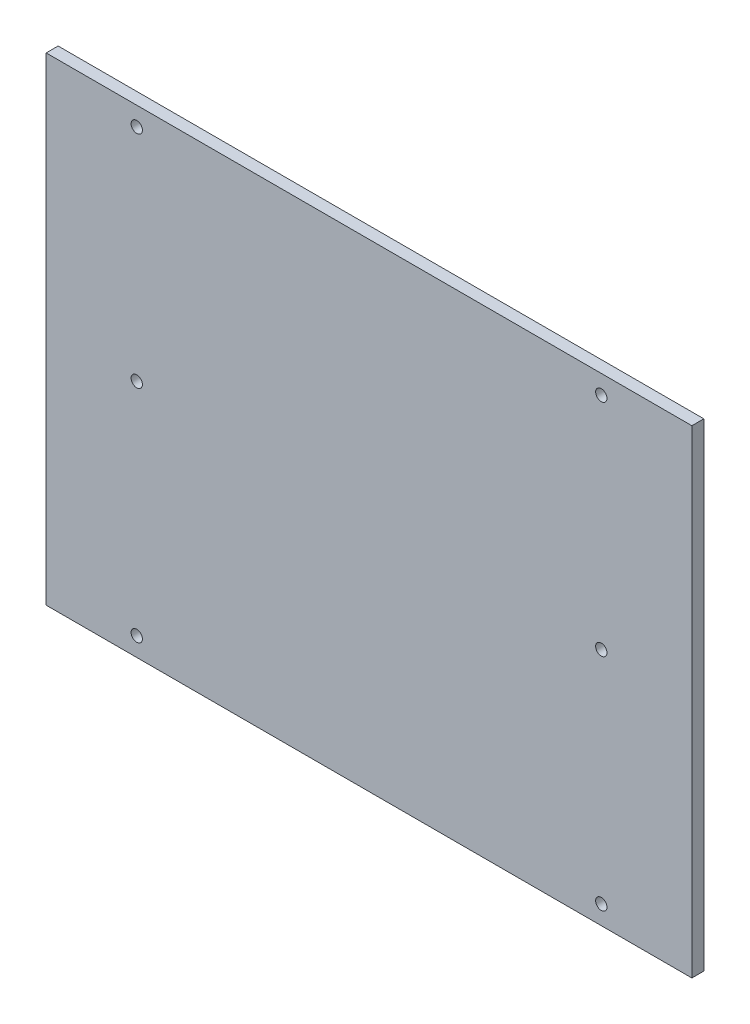
SolidWorks part; units mm, degrees
material "Acrylic (Medium-high impact)"
ref_plane "Front Plane" through (0, 0, 0) normal (0, 0, 1) x (1, 0, 0)
ref_plane "Top Plane" through (0, 0, 0) normal (0, 1, 0) x (1, 0, 0)
ref_plane "Right Plane" through (0, 0, 0) normal (1, 0, 0) x (0, 0, -1)
sketch "Sketch1" plane through (0, 0, 0) normal (0, 0, 1) x (1, 0, 0)
  line L0 (0, 0) -> (0, 127)
  line L1 (0, 127) -> (133.35, 127)
  line L2 (133.35, 127) -> (133.35, 0)
  line L3 (133.35, 0) -> (0, 0)
  line L8 (66.675, 127) -> (66.675, 0) construction
  line L9 (0, 63.5) -> (133.35, 63.5) construction
  circle A0 centre (5, 5) radius 1.5
  circle A1 centre (5, 122) radius 1.5
  circle A4 centre (5, 63.5) radius 1.5
  circle A5 centre (128.35, 122) radius 1.5
  circle A6 centre (128.35, 63.5) radius 1.5
  circle A7 centre (128.35, 5) radius 1.5
  dimension "D7" = 3
  dimension "D10" = 3
  dimension "D2" = 133.35
  dimension "D3" = 127
  dimension "D8" = 5
  dimension "D9" = 5
extrude "Boss-Extrude1" add sketch "Sketch1" along normal blind 3.175
sketch "Sketch2" [suppressed] plane through (0, 0, 3.175) normal (0, 0, 1) x (1, 0, 0)
  line L0 (10, 10) -> (10, 159.3333)
  line L1 (10, 159.3333) -> (123.35, 159.3333)
  line L2 (123.35, 159.3333) -> (123.35, 10)
  line L3 (123.35, 10) -> (10, 10)
  line L4 (0, 0) -> (133.35, 0) construction
  line L5 (0, 169.3333) -> (0, 0) construction
  line L6 (133.35, 0) -> (133.35, 169.3333) construction
  line L7 (133.35, 169.3333) -> (0, 169.3333) construction
  dimension "D1" = 10
  dimension "D2" = 10
  dimension "D3" = 10
  dimension "D4" = 127
extrude "Cut-Extrude1" [suppressed] cut sketch "Sketch2" against normal up to surface (3.175 mm away)
sketch "Sketch3" plane through (0, 0, 3.175) normal (0, 0, 1) x (1, 0, 0)
  line L0 (66.675, 0) -> (66.675, 127) construction
  line L1 (0, 0) -> (133.35, 0) construction
  line L2 (133.35, 127) -> (0, 127) construction
  line L3 (0, 127) -> (-19.05, 127)
  line L4 (-19.05, 127) -> (-19.05, 0)
  line L5 (-19.05, 0) -> (0, 0)
  line L6 (0, 0) -> (0, 127)
  line L7 (152.4, 0) -> (133.35, 0)
  line L8 (152.4, 127) -> (152.4, 0)
  line L9 (133.35, 127) -> (152.4, 127)
  line L10 (133.35, 0) -> (133.35, 127)
  dimension "D1" = 171.45
extrude "Boss-Extrude2" add sketch "Sketch3" against normal up to surface (3.175 mm away) up to face at (126.85, 63.5, 0)
